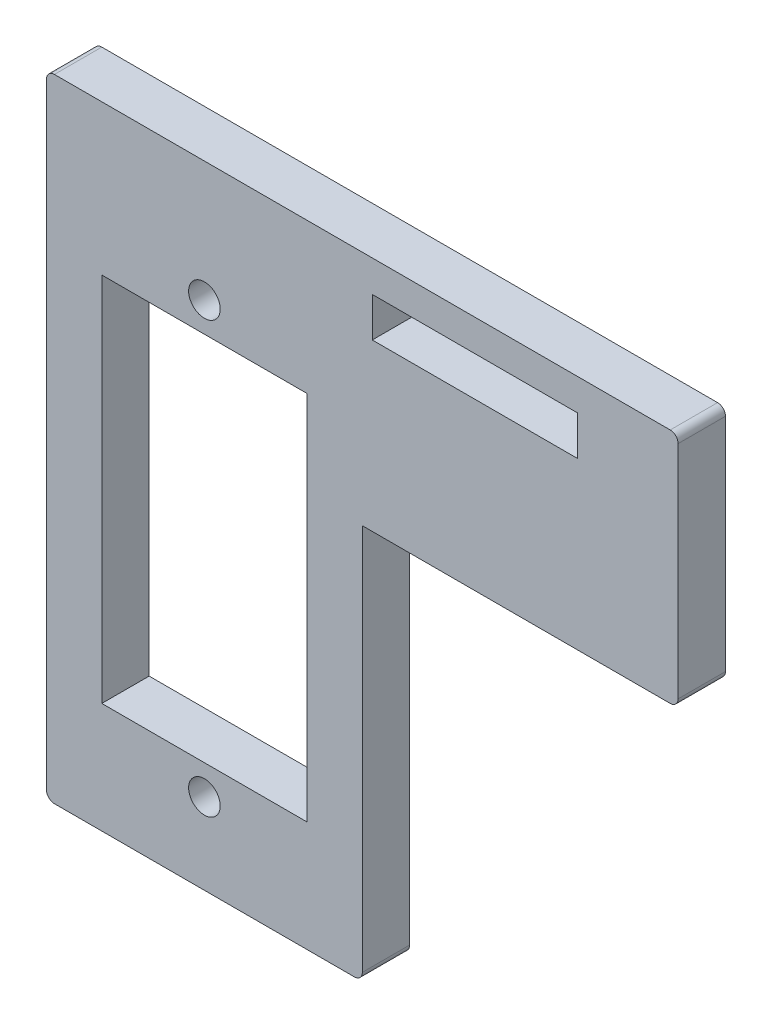
SolidWorks part; units mm, degrees
ref_plane "Ön Düzlem" through (0, 0, 0) normal (0, 0, 1) x (1, 0, 0)
ref_plane "Üst Düzlem" through (0, 0, 0) normal (0, 1, 0) x (1, 0, 0)
ref_plane "Sağ Düzlem" through (0, 0, 0) normal (1, 0, 0) x (0, 0, -1)
sketch "Çizim1" plane through (0, 0, 0) normal (0, 0, 1) x (1, 0, 0)
  line L0 (-39.3368, 0) -> (31.0415, 0) construction
  line L1 (-6.5, 11.75) -> (6.5, 11.75)
  line L2 (-6.5, 11.75) -> (-6.5, -11.75)
  line L3 (-6.5, -11.75) -> (6.5, -11.75)
  line L4 (6.5, 11.75) -> (6.5, -11.75)
  line L5 (0, 22.9268) -> (0, -17.1596) construction
  line L6 (10, 21.25) -> (30, 21.25)
  line L7 (-10, 21.25) -> (10, 21.25)
  line L8 (-10, 21.25) -> (-10, -18.75)
  line L9 (-10, -18.75) -> (10, -18.75)
  line L10 (10, 6.25) -> (10, -18.75)
  line L11 (30, 21.25) -> (30, 6.25)
  line L12 (30, 6.25) -> (10, 6.25)
  dimension "D1" = 23.5
  dimension "D2" = 13
  dimension "D3" = 40
  dimension "D4" = 20
  dimension "D5" = 20
  dimension "D6" = 15
  dimension "D7" = 7
extrude "Yükseklik-Ekstrüzyon1" add sketch "Çizim1" along normal blind 3
fillet "Radyus1" radius 0.5 5 edges at (-10, 21.25, 1.5) (-10, -18.75, 1.5) (10, -18.75, 1.5) (30, 6.25, 1.5) (30, 21.25, 1.5)
sketch "Çizim5" plane through (0, 0, 0) normal (0, 0, -1) x (-1, 0, 0)
  circle A0 centre (0, 13.625) radius 1
  circle A1 centre (0, -13.625) radius 1
extrude "Kes-Ekstrüzyon1" cut sketch "Çizim5" against normal up to next
sketch "Çizim6" plane through (0, 0, 0) normal (0, 0, -1) x (-1, 0, 0)
  line L0 (-29.5, 21.25) -> (9.5, 21.25) construction
  line L1 (-23.6302, 19.25) -> (-10.6302, 19.25)
  line L2 (-23.6302, 19.25) -> (-23.6302, 16.75)
  line L3 (-23.6302, 16.75) -> (-10.6302, 16.75)
  line L4 (-10.6302, 19.25) -> (-10.6302, 16.75)
  dimension "D1" = 13
  dimension "D2" = 2.5
  dimension "D3" = 2
extrude "Kes-Ekstrüzyon2" cut sketch "Çizim6" against normal up to next
